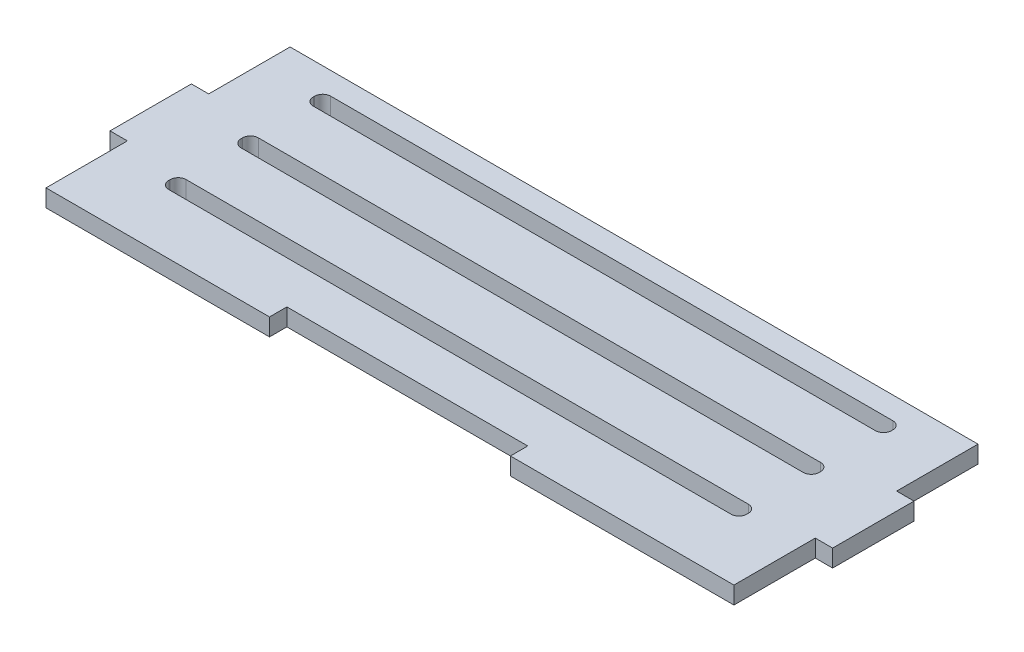
SolidWorks part; units mm, degrees
ref_plane "Front Plane" through (0, 0, 0) normal (0, 0, 1) x (1, 0, 0)
ref_plane "Top Plane" through (0, 0, 0) normal (0, 1, 0) x (1, 0, 0)
ref_plane "Right Plane" through (0, 0, 0) normal (1, 0, 0) x (0, 0, -1)
sketch "Sketch1" plane through (0, 0, 0) normal (0, 1, 0) x (1, 0, 0)
  line L1 (0, 0) -> (500, 0)
  line L2 (0, 0) -> (0, 168.89)
  line L3 (0, 168.89) -> (500, 168.89)
  line L4 (500, 0) -> (500, 168.89)
  dimension "D1" = 500
  dimension "D2" = 168.89
extrude "Boss-Extrude1" add sketch "Sketch1" along normal blind 12
sketch "Sketch2" plane through (0, 12, 0) normal (0, 1, 0) x (1, 0, 0)
  line L5 (0, 0) -> (500, 0) construction
  line L6 (166.6667, 0) -> (333.3333, 0)
  line L7 (166.6667, 0) -> (166.6667, 12)
  line L8 (166.6667, 12) -> (333.3333, 12)
  line L9 (333.3333, 0) -> (333.3333, 12)
  line L10 (0, 168.89) -> (0, 0) construction
  dimension "D1" = 12
  dimension "D4" = 166.6667
extrude "Cut-Extrude1" cut sketch "Sketch2" against normal through all
sketch "Sketch4" plane through (0, 12, 0) normal (0, 1, 0) x (1, 0, 0)
  line L1 (0, 168.89) -> (12, 168.89)
  line L2 (0, 168.89) -> (0, 112.5933)
  line L3 (0, 112.5933) -> (12, 112.5933)
  line L4 (12, 168.89) -> (12, 112.5933)
  line L5 (0, 0) -> (12, 0)
  line L6 (0, 0) -> (0, 56.2967)
  line L7 (0, 56.2967) -> (12, 56.2967)
  line L8 (12, 0) -> (12, 56.2967)
  line L9 (500, 0) -> (488, 0)
  line L10 (500, 0) -> (500, 56.2967)
  line L11 (500, 56.2967) -> (488, 56.2967)
  line L12 (488, 0) -> (488, 56.2967)
  line L13 (500, 168.89) -> (488, 168.89)
  line L14 (500, 168.89) -> (500, 112.5933)
  line L15 (500, 112.5933) -> (488, 112.5933)
  line L16 (488, 168.89) -> (488, 112.5933)
  dimension "D1" = 12
  dimension "D2" = 56.2967
extrude "Cut-Extrude3" cut sketch "Sketch4" against normal through all
sketch "Sketch5" plane through (0, 12, 0) normal (0, 1, 0) x (1, 0, 0)
  line L1 (55.5, 153.4495) -> (444.5, 153.4495)
  line L2 (50, 147.9495) -> (50, 146.9495)
  line L3 (55.5, 141.4495) -> (444.5, 141.4495)
  line L4 (450, 147.9495) -> (450, 146.9495)
  line L6 (12, 112.5933) -> (12, 168.89) construction
  arc A0 (444.5, 141.4495) -> (450, 146.9495) centre (444.5, 146.9495) ccw
  arc A1 (444.5, 153.4495) -> (450, 147.9495) centre (444.5, 147.9495) cw
  arc A2 (50, 146.9495) -> (55.5, 141.4495) centre (55.5, 146.9495) ccw
  arc A3 (55.5, 153.4495) -> (50, 147.9495) centre (55.5, 147.9495) ccw
  point P11 (450, 153.4495)
  point P14 (50, 141.4495)
  point P17 (50, 153.4495)
  dimension "D4" = 5.5
  dimension "D1" = 400
  dimension "D2" = 38
  dimension "D3" = 12
extrude "Cut-Extrude4" cut sketch "Sketch5" against normal through all
pattern_linear "LPattern1" count 3 spacing 50 along (0, 0, 1) of "Cut-Extrude4"
scale "Scale1" scale about centroid uniform scaling yes scale factor 0.5
